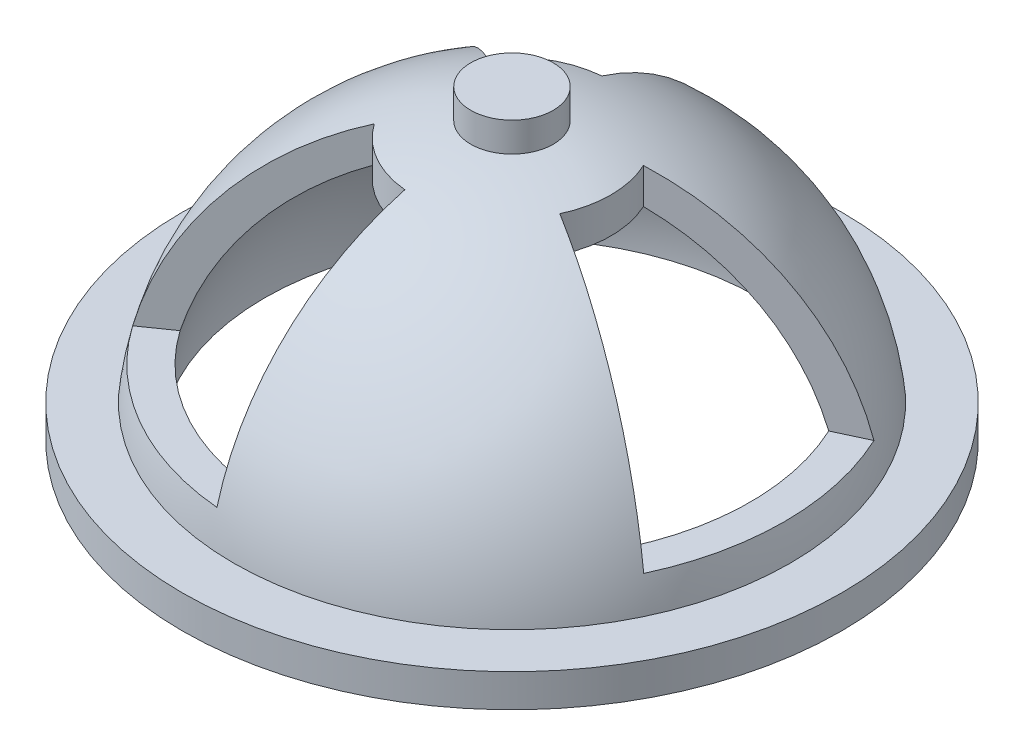
SolidWorks part; units mm, degrees
ref_plane "前视基准面" through (0, 0, 0) normal (0, 0, 1) x (1, 0, 0)
ref_plane "上视基准面" through (0, 0, 0) normal (0, 1, 0) x (1, 0, 0)
ref_plane "右视基准面" through (0, 0, 0) normal (1, 0, 0) x (0, 0, -1)
other "Configuration Table"
sketch "草图1" plane through (0, 0, 0) normal (0, 0, 1) x (1, 0, 0)
  line L0 (0, 77.8892) -> (0, -61.5929) construction
  line L1 (-114.9501, 0) -> (97.252, 0) construction
  line L2 (0, 37.5) -> (0, 46.5)
  line L3 (0, 46.5) -> (6.25, 46.5)
  line L4 (6.25, 46.5) -> (6.25, 42.0379)
  line L5 (42.2049, 5) -> (50, 5)
  line L6 (50, 5) -> (50, 0)
  line L7 (50, 0) -> (37.5, 0)
  arc A0 (0, 37.5) -> (37.5, 0) centre (0, 0) cw
  arc A1 (6.25, 42.0379) -> (42.2049, 5) centre (0, 0) cw
  arc A2 (0, 42.5) -> (42.5, 0) centre (0, 0) cw construction
  point P19 (0.5872, 46.5)
  dimension "D3" = 42.5
  dimension "D2" = 100
  dimension "D4" = 5
  dimension "D5" = 46.5
  dimension "D6" = 12.5
  dimension "D1" = 5
revolve "旋转1" add sketch "草图1" angle 360 about L2
sketch "草图2" plane through (0, 0, 0) normal (0, 0, 1) x (1, 0, 0)
  line L0 (0, 61.6747) -> (0, -15.1856) construction
  line L1 (15, 39.7649) -> (15, 34.3693)
  line L2 (41.3068, 10) -> (36.1421, 10)
  line L3 (-50, 0) -> (50, 0) construction
  arc A0 (42.2049, 5) -> (6.25, 42.0379) centre (0, 0) ccw construction
  arc A1 (37.5, 0) -> (-37.5, 0) centre (0, 0) ccw construction
  arc A2 (41.3068, 10) -> (15, 39.7649) centre (0, 0) ccw
  arc A3 (36.1421, 10) -> (15, 34.3693) centre (0, 0) ccw
  dimension "D1" = 15
  dimension "D2" = 10
revolve "切除-旋转1" cut sketch "草图2" angle 50 mid plane about L0
pattern_circular "阵列(圆周)1" count 3 over 360 about axis through (0, 0, 0) along (0, 1, 0) of "切除-旋转1"
